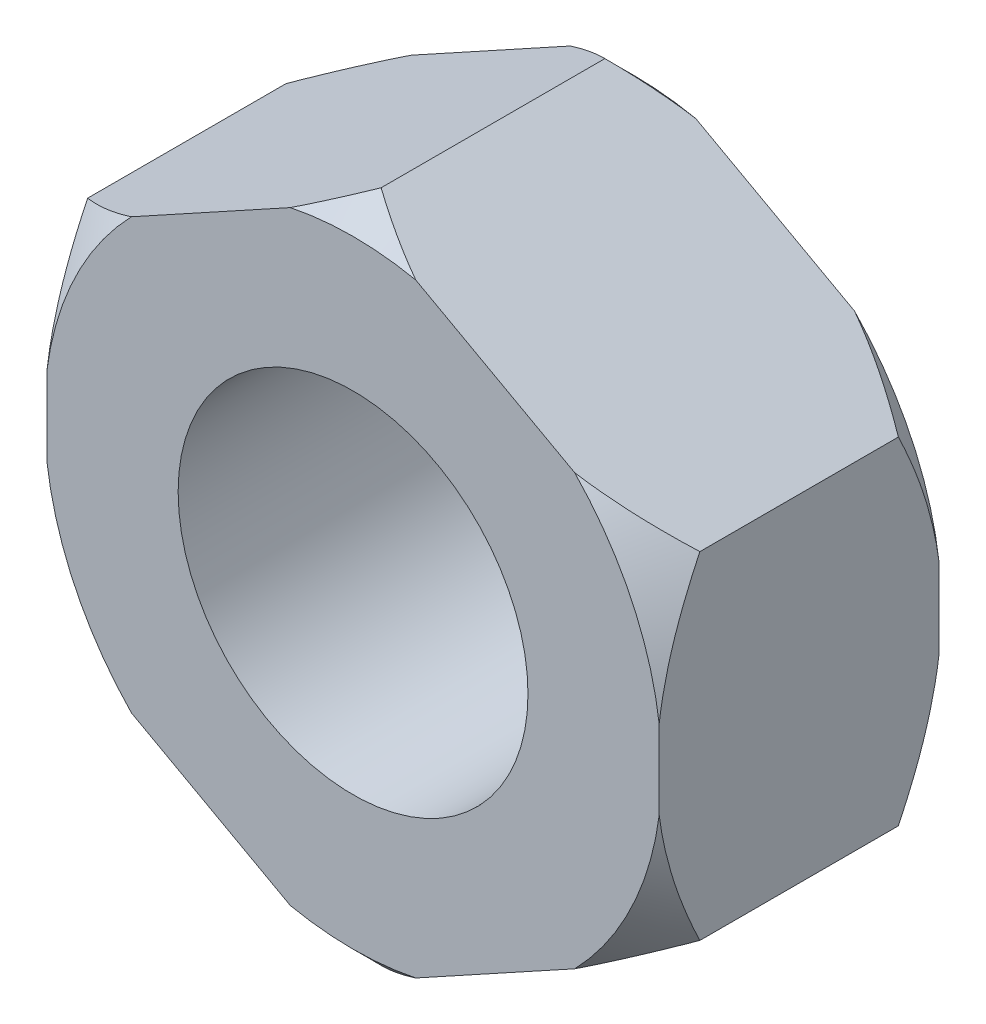
SolidWorks part; units mm, degrees
ref_plane "Front Plane" through (0, 0, 0) normal (0, 0, 1) x (1, 0, 0)
ref_plane "Top Plane" through (0, 0, 0) normal (0, 1, 0) x (1, 0, 0)
ref_plane "Right Plane" through (0, 0, 0) normal (1, 0, 0) x (0, 0, -1)
sketch "Sketch1" plane through (0, 0, 0) normal (0, 0, 1) x (1, 0, 0)
  line L0 (0, 0) -> (0, 3.85) construction
  line L1 (-3.5, -1.925) -> (-3.5, 1.925)
  line L2 (0, 0) -> (0, -3.85) construction
  line L3 (0, 0) -> (-3.5, 0) construction
  line L4 (3.5, -1.925) -> (3.5, 1.925)
  line L5 (-3.5, 1.925) -> (0, 3.85)
  line L6 (0, 3.85) -> (3.5, 1.925)
  line L7 (3.5, -1.925) -> (0, -3.85)
  line L8 (0, -3.85) -> (-3.5, -1.925)
  circle A0 centre (0, 0) radius 2
  dimension "THREAD SIZE" = 4
  dimension "LENGTH (A)" = 7
  dimension "D3" = 1.925
  dimension "D4" = 1.925
  dimension "HEIGHT (B)" = 7.7
  dimension "D1" = 3.85
  dimension "D2" = 3.5
  dimension "D5" = 3.85
  dimension "D6" = 90
extrude "NUT" add sketch "Sketch1" along normal blind 3.2
sketch "Sketch2" plane through (0, 0, 0) normal (1, 0, 0) x (0, 0, -1)
  line L0 (-3.2, 3.5292) -> (-2.4428, 4.2864)
  line L1 (-3.2, 1.925) -> (-3.2, 3.85) construction
  line L2 (-3.2, 3.85) -> (0, 3.85) construction
  line L3 (-3.2, 3.5292) -> (-3.2, 3.85)
  line L4 (0, 4.2864) -> (-0.7572, 4.2864)
  line L5 (-1.6, 3.85) -> (-1.6, 1.4914) construction
  line L6 (0, 3.85) -> (0, 4.2864)
  line L7 (0, 3.5292) -> (0, 3.85)
  line L8 (-3.2, 3.85) -> (-3.2, 4.2864)
  line L9 (0, 3.5292) -> (-0.7572, 4.2864)
  line L10 (-3.2, 4.2864) -> (-2.4428, 4.2864)
  dimension "D2" = 0.3208
  dimension "D3" = 45
  dimension "D1" = 1.0708
revolve "Cut-Revolve1" cut sketch "Sketch2" angle 360 about axis through (0, 0, 3.2) along (0, 0, -1)
equation "\"D3@Sketch1\" = \"HEIGHT (B)@Sketch1\" / 4"
equation "\"D4@Sketch1\" = \"HEIGHT (B)@Sketch1\" / 4"
equation "\"D1@Sketch1\" = \"HEIGHT (B)@Sketch1\" / 2"
equation "\"D2@Sketch1\" = \"LENGTH (A)@Sketch1\" / 2"
equation "\"D5@Sketch1\" = \"D1@Sketch1\""
equation "\"D2@Sketch2\" = \"HEIGHT (B)@Sketch1\" / 24"
equation "\"D1@Sketch2\" = \"D2@Sketch2\" + .75"
